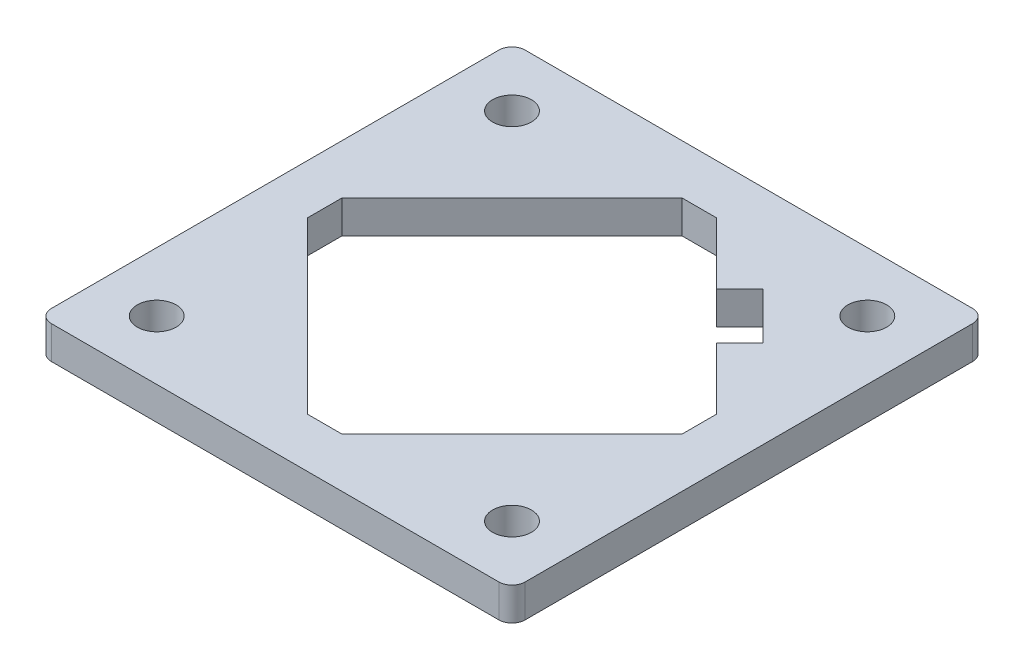
SolidWorks part; units mm, degrees
ref_plane "Front" through (0, 0, 0) normal (0, 0, 1) x (1, 0, 0)
ref_plane "Top" through (0, 0, 0) normal (0, 1, 0) x (1, 0, 0)
ref_plane "Right" through (0, 0, 0) normal (1, 0, 0) x (0, 0, -1)
sketch "Sketch1" plane through (0, 0, 0) normal (0, 1, 0) x (1, 0, 0)
  line L0 (-28.461, -2.6517) -> (-2.6517, -28.461)
  line L1 (-36, -36) -> (36, -36)
  line L2 (-36, -36) -> (-36, 36)
  line L3 (-36, 36) -> (36, 36)
  line L4 (36, -36) -> (36, 36)
  line L5 (-36, -36) -> (36, 36) construction
  line L6 (-36, 36) -> (36, -36) construction
  line L7 (2.6517, -28.461) -> (28.461, -2.6517)
  line L8 (28.461, 2.6517) -> (19.0919, 12.0208)
  line L9 (-2.6517, 28.461) -> (-28.461, 2.6517)
  line L10 (-2.6517, -28.461) -> (2.6517, -28.461)
  line L11 (28.461, -2.6517) -> (28.461, 2.6517)
  line L12 (-2.6517, 28.461) -> (2.6517, 28.461)
  line L13 (-28.461, 2.6517) -> (-28.461, -2.6517)
  line L14 (12.0208, 19.0919) -> (15.5563, 22.6274)
  line L15 (15.5563, 22.6274) -> (22.6274, 15.5563)
  line L16 (22.6274, 15.5563) -> (19.0919, 12.0208)
  line L17 (12.0208, 19.0919) -> (2.6517, 28.461)
  circle A0 centre (-27, 27) radius 2.95
  circle A1 centre (27, -27) radius 2.95
  circle A2 centre (-27, -27) radius 2.95
  circle A3 centre (27, 27) radius 2.95
  point P0 (0, 0)
  point P7 (0, 28.461)
  point P8 (28.461, 0)
  point P19 (19.0919, 19.0919)
  dimension "D6" = 5.9
  dimension "D1" = 72
  dimension "D2" = 44
  dimension "D3" = 36.5
  dimension "D4" = 5
  dimension "D5" = 10
  dimension "D7" = 9
extrude "Boss-Extrude1" add sketch "Sketch1" along normal blind 5
fillet "Fillet1" radius 2 4 edges at (-36, 2.5, 36) (36, 2.5, 36) (36, 2.5, -36) (-36, 2.5, -36)
